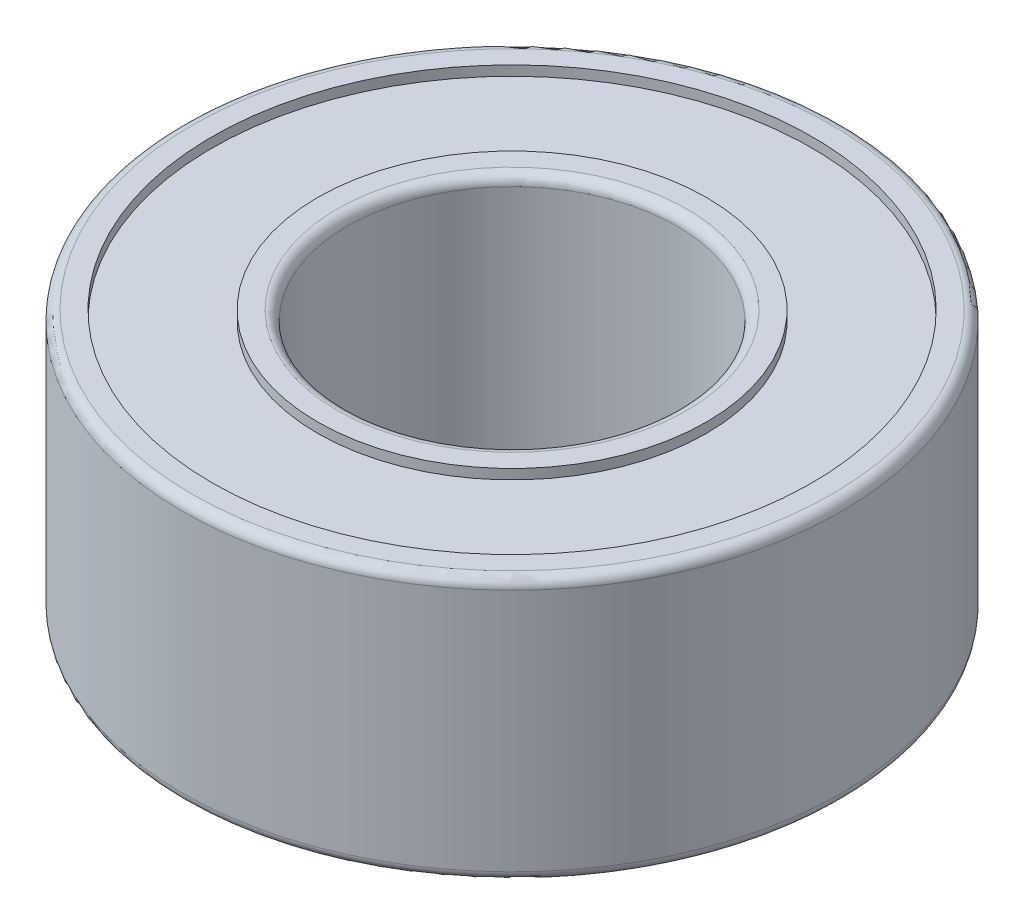
SolidWorks part; units mm, degrees
ref_plane "Plan de face" through (0, 0, 0) normal (0, 0, 1) x (1, 0, 0)
ref_plane "Plan de dessus" through (0, 0, 0) normal (0, 1, 0) x (1, 0, 0)
ref_plane "Plan de droite" through (0, 0, 0) normal (1, 0, 0) x (0, 0, -1)
ref_plane "Plan1" through (0, 0, 0) normal (0, 0, -1) x (-1, 0, 0)
sketch "Esquisse1" plane through (0, 0, 0) normal (0, 0, -1) x (-1, 0, 0)
  line L0 (-2.5, -1.85) -> (-2.5, 1.85)
  line L1 (-2.65, 2) -> (-2.95, 2)
  line L2 (-2.95, 2) -> (-2.95, 1.85)
  line L3 (-2.95, 1.85) -> (-4.55, 1.85)
  line L4 (-4.55, 1.85) -> (-4.55, 2)
  line L5 (-4.55, 2) -> (-4.85, 2)
  line L6 (-5, 1.85) -> (-5, -1.85)
  line L7 (-4.85, -2) -> (-4.55, -2)
  line L8 (-4.55, -2) -> (-4.55, -1.85)
  line L9 (-4.55, -1.85) -> (-2.95, -1.85)
  line L10 (-2.95, -1.85) -> (-2.95, -2)
  line L11 (-2.95, -2) -> (-2.65, -2)
  line L12 (0, -2.0034) -> (0, 2.0034) construction
  line L13 (-3.75, 2.3933) -> (-3.75, -2.4549) construction
  arc A0 (-2.65, -2) -> (-2.5, -1.85) centre (-2.65, -1.85) ccw
  arc A1 (-2.5, 1.85) -> (-2.65, 2) centre (-2.65, 1.85) ccw
  arc A2 (-4.85, 2) -> (-5, 1.85) centre (-4.85, 1.85) ccw
  arc A3 (-4.85, -2) -> (-5, -1.85) centre (-4.85, -1.85) cw
  point P24 (-3.75, -1.85)
  point P25 (-2.5, 0)
  dimension "D1" = 0.15
  dimension "D2" = 5
  dimension "D3" = 10
  dimension "D4" = 4
  dimension "D5" = 0.15
  dimension "D6" = 1.6
revolve "Révolution1" add sketch "Esquisse1" angle 360 about L12
